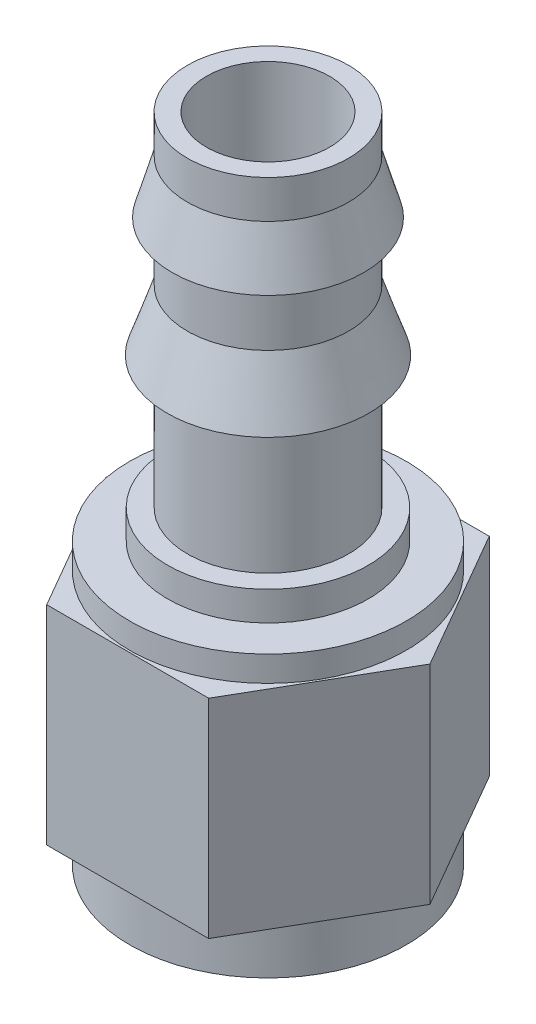
SolidWorks part; units mm, degrees
ref_plane "Front Plane" through (0, 0, 0) normal (0, 0, 1) x (1, 0, 0)
ref_plane "Top Plane" through (0, 0, 0) normal (0, 1, 0) x (1, 0, 0)
ref_plane "Right Plane" through (0, 0, 0) normal (1, 0, 0) x (0, 0, -1)
sketch "Sketch1" plane through (0, 0, 0) normal (0, 0, 1) x (1, 0, 0)
  line L0 (0, 51.4) -> (0, 0)
  line L1 (0, 0) -> (10.9, 0)
  line L2 (10.9, 0) -> (10.9, 3.8)
  line L3 (10.9, 3.8) -> (11.05, 3.8)
  line L4 (11.05, 3.8) -> (11.05, 20.1)
  line L6 (10.9, 20.1) -> (10.9, 22.1)
  line L7 (11.05, 20.1) -> (10.9, 20.1)
  line L9 (10.9, 22.1) -> (7.9, 22.1)
  line L10 (7.9, 22.1) -> (7.9, 24.4)
  line L12 (7.9, 24.4) -> (6.35, 24.4)
  line L13 (6.35, 24.4) -> (6.35, 34.8)
  line L14 (6.35, 34.8) -> (7.95, 34.8)
  line L16 (7.95, 34.8) -> (6.35, 39.6)
  line L17 (6.35, 39.6) -> (6.35, 44.2)
  line L18 (6.35, 44.2) -> (7.55, 44.2)
  line L19 (6.35, 48.4) -> (6.35, 51.4)
  line L20 (7.55, 44.2) -> (6.35, 48.4)
  line L22 (0, 51.4) -> (6.35, 51.4)
revolve "Revolve1" add sketch "Sketch1" angle 360 about L0
sketch "Sketch2" plane through (0, 20.1, 0) normal (0, 1, 0) x (1, 0, 0)
  line L1 (12.7618, 0) -> (6.3809, 11.0521)
  line L2 (6.3809, 11.0521) -> (-6.3809, 11.0521)
  line L3 (-6.3809, 11.0521) -> (-12.7618, 0)
  line L4 (-12.7618, 0) -> (-6.3809, -11.0521)
  line L5 (-6.3809, -11.0521) -> (6.3809, -11.0521)
  line L6 (6.3809, -11.0521) -> (12.7618, 0)
  circle A0 centre (0, 0) radius 11.0521 construction
extrude "Boss-Extrude1" add sketch "Sketch2" against normal blind 16.4
sketch "Sketch3" plane through (0, 51.4, 0) normal (0, 1, 0) x (1, 0, 0)
  circle A0 centre (0, 0) radius 4.85
extrude "Cut-Extrude1" cut sketch "Sketch3" against normal through all
